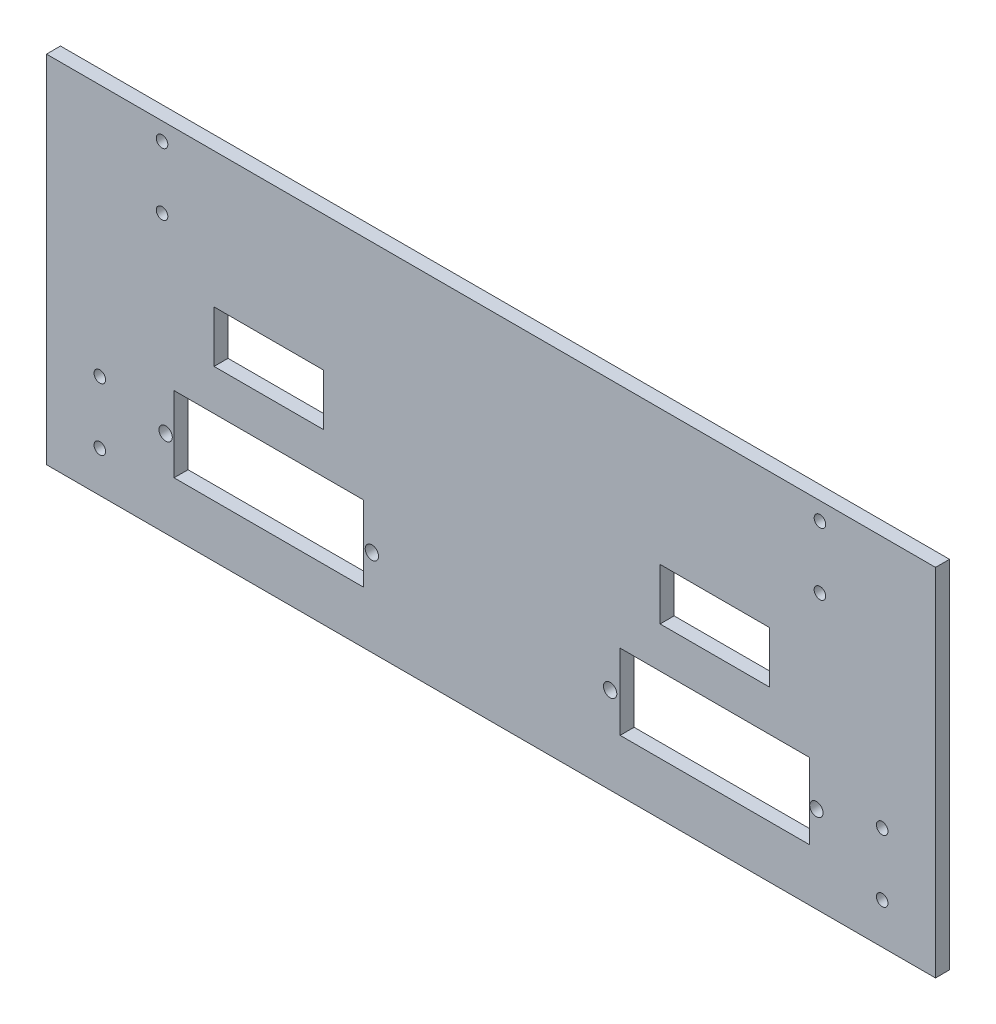
SolidWorks part; units mm, degrees
ref_plane "Front Plane" through (0, 0, 0) normal (0, 0, 1) x (1, 0, 0)
ref_plane "Top Plane" through (0, 0, 0) normal (0, 1, 0) x (1, 0, 0)
ref_plane "Right Plane" through (0, 0, 0) normal (1, 0, 0) x (0, 0, -1)
sketch "Sketch1" plane through (0, 0, 0) normal (0, 0, 1) x (1, 0, 0)
  line L1 (0, 0) -> (0, 101.6)
  line L3 (254, 101.6) -> (254, 0)
  line L4 (0, 0) -> (15.24, 0) construction
  line L5 (63.5, 0) -> (63.5, 12.7) construction
  line L6 (63.5, 12.7) -> (98.552, 12.7) construction
  line L12 (28.448, 36.83) -> (98.552, 36.83) construction
  line L22 (0, 101.6) -> (33.02, 101.6) construction
  line L23 (33.02, 101.6) -> (39.624, 101.6) construction
  line L24 (39.624, 101.6) -> (39.624, 65.532) construction
  line L25 (39.624, 65.532) -> (26.416, 65.532) construction
  line L26 (26.416, 65.532) -> (26.416, 101.6) construction
  line L27 (26.416, 101.6) -> (33.02, 101.6) construction
  line L28 (33.02, 78.74) -> (33.02, 101.6) construction
  line L29 (33.02, 78.74) -> (33.02, 96.52) construction
  line L30 (254, 101.6) -> (220.98, 101.6) construction
  line L31 (220.98, 101.6) -> (214.376, 101.6) construction
  line L32 (214.376, 101.6) -> (214.376, 65.532) construction
  line L38 (214.376, 65.532) -> (227.584, 65.532) construction
  line L39 (227.584, 65.532) -> (227.584, 101.6) construction
  line L40 (98.552, 36.83) -> (98.552, 12.7) construction
  line L41 (63.5, 12.7) -> (28.448, 12.7) construction
  line L42 (28.448, 12.7) -> (28.448, 36.83) construction
  line L43 (63.5, 12.7) -> (63.5, 14.986) construction
  line L44 (28.448, 24.765) -> (34.036, 24.765) construction
  line L45 (98.552, 24.765) -> (92.964, 24.765) construction
  line L46 (63.5, 14.986) -> (90.551, 14.986)
  line L47 (90.551, 14.986) -> (90.551, 36.576)
  line L48 (90.551, 36.576) -> (36.449, 36.576)
  line L49 (36.449, 36.576) -> (36.449, 14.986)
  line L50 (36.449, 14.986) -> (63.5, 14.986)
  line L51 (254, 0) -> (238.76, 0) construction
  line L52 (190.5, 0) -> (190.5, 12.7) construction
  line L53 (190.5, 12.7) -> (190.5, 14.9805) construction
  line L54 (190.5, 12.7) -> (225.552, 12.7) construction
  line L55 (225.552, 12.7) -> (225.552, 36.83) construction
  line L56 (225.552, 36.83) -> (155.448, 36.83) construction
  line L57 (155.448, 36.83) -> (155.448, 12.7) construction
  line L58 (155.448, 12.7) -> (190.5, 12.7) construction
  line L59 (155.448, 24.765) -> (161.036, 24.765) construction
  line L60 (225.552, 24.765) -> (219.964, 24.765) construction
  line L61 (190.5, 14.9805) -> (217.9923, 14.9805)
  line L62 (217.9923, 14.9805) -> (217.9923, 36.5705)
  line L63 (217.9923, 36.5705) -> (163.8903, 36.5705)
  line L64 (163.8903, 36.5705) -> (163.8903, 14.9805)
  line L65 (163.8903, 14.9805) -> (190.5, 14.9805)
  line L66 (220.98, 101.6) -> (220.98, 78.74) construction
  line L67 (220.98, 78.74) -> (220.98, 96.52) construction
  line L68 (0, 101.6) -> (254, 101.6)
  line L69 (15.24, 0) -> (15.24, 11.684) construction
  line L70 (15.24, 11.684) -> (15.24, 29.464) construction
  line L71 (238.76, 0) -> (238.76, 11.684) construction
  line L72 (238.76, 11.684) -> (238.76, 29.464) construction
  line L73 (0, 0) -> (254, 0)
  line L74 (63.5, 36.576) -> (63.5, 55.626) construction
  line L75 (190.9413, 55.626) -> (190.9413, 36.5705) construction
  line L76 (47.879, 62.992) -> (79.121, 62.992)
  line L77 (47.879, 62.992) -> (47.879, 48.26)
  line L78 (47.879, 48.26) -> (79.121, 48.26)
  line L79 (79.121, 62.992) -> (79.121, 48.26)
  line L80 (47.879, 62.992) -> (79.121, 48.26) construction
  line L81 (47.879, 48.26) -> (79.121, 62.992) construction
  line L82 (175.3203, 62.992) -> (206.5623, 62.992)
  line L83 (175.3203, 62.992) -> (175.3203, 48.26)
  line L84 (175.3203, 48.26) -> (206.5623, 48.26)
  line L85 (206.5623, 62.992) -> (206.5623, 48.26)
  line L86 (175.3203, 62.992) -> (206.5623, 48.26) construction
  line L87 (175.3203, 48.26) -> (206.5623, 62.992) construction
  line L88 (63.5, 55.626) -> (190.9413, 55.626) construction
  circle A6 centre (34.036, 24.765) radius 1.905
  circle A7 centre (92.964, 24.765) radius 1.905
  circle A8 centre (161.036, 24.765) radius 1.905
  circle A9 centre (219.964, 24.765) radius 1.905
  circle A10 centre (33.02, 78.74) radius 1.651
  circle A11 centre (33.02, 96.52) radius 1.651
  circle A12 centre (220.98, 78.74) radius 1.651
  circle A13 centre (220.98, 96.52) radius 1.651
  circle A14 centre (15.24, 11.684) radius 1.651
  circle A15 centre (15.24, 29.464) radius 1.651
  circle A16 centre (238.76, 29.464) radius 1.651
  circle A17 centre (238.76, 11.684) radius 1.651
  point P69 (63.5, 55.626)
  point P75 (190.9413, 55.626)
  dimension "D1" = 254
  dimension "D5" = 70.104
  dimension "D14" = 54.102
  dimension "D7" = 21.59
  dimension "D8" = 3.81
  dimension "D15" = 70.104
  dimension "D17" = 3.81
  dimension "D10" = 22.86
  dimension "D19" = 17.78
  dimension "D22" = 14.732
  dimension "D2" = 101.6
  dimension "D3" = 12.7
  dimension "D4" = 24.13
  dimension "D6" = 2.286
  dimension "D9" = 33.02
  dimension "D11" = 17.78
  dimension "D12" = 33.02
  dimension "D13" = 6.604
  dimension "D16" = 24.13
  dimension "D18" = 5.588
  dimension "D20" = 11.684
  dimension "D21" = 15.24
  dimension "D23" = 31.242
  dimension "D24" = 31.242
  dimension "D25" = 14.732
extrude "Boss-Extrude1" add sketch "Sketch1" along normal blind 4
